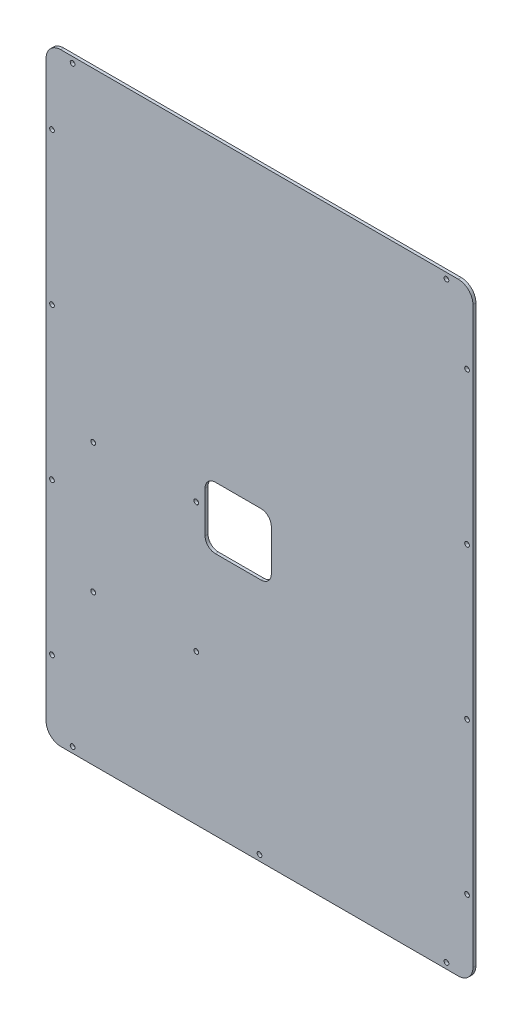
SolidWorks part; units mm, degrees
ref_plane "前视基准面" through (0, 0, 0) normal (0, 0, 1) x (1, 0, 0)
ref_plane "上视基准面" through (0, 0, 0) normal (0, 1, 0) x (1, 0, 0)
ref_plane "右视基准面" through (0, 0, 0) normal (1, 0, 0) x (0, 0, -1)
sketch "草图1" plane through (0, 0, 0) normal (0, 0, 1) x (1, 0, 0)
  line L1 (-58.971, 258.2107) -> (211.029, 258.2107)
  line L2 (-68.971, 248.2107) -> (-68.971, -141.7893)
  line L3 (-58.971, -151.7893) -> (211.029, -151.7893)
  line L4 (221.029, 248.2107) -> (221.029, -141.7893)
  arc A0 (-68.971, -141.7893) -> (-58.971, -151.7893) centre (-58.971, -141.7893) ccw
  arc A1 (211.029, -151.7893) -> (221.029, -141.7893) centre (211.029, -141.7893) ccw
  arc A2 (211.029, 258.2107) -> (221.029, 248.2107) centre (211.029, 248.2107) cw
  arc A3 (-58.971, 258.2107) -> (-68.971, 248.2107) centre (-58.971, 248.2107) ccw
  point P6 (-68.971, -151.7893)
  point P9 (221.029, -151.7893)
  point P14 (-68.971, 258.2107)
  dimension "D3" = 10
  dimension "D1" = 290
  dimension "D2" = 410
extrude "凸台-拉伸1" add sketch "草图1" along normal blind 2
sketch "草图2" plane through (0, 0, 2) normal (0, 0, 1) x (1, 0, 0)
  line L0 (-68.971, 248.2107) -> (-68.971, -141.7893) construction
  line L1 (211.029, 258.2107) -> (-58.971, 258.2107) construction
  line L2 (221.029, -141.7893) -> (221.029, 248.2107) construction
  line L3 (-58.971, -151.7893) -> (211.029, -151.7893) construction
  circle A0 centre (-64.971, 208.2107) radius 1.6
  circle A1 centre (-64.971, 105.2107) radius 1.6
  circle A2 centre (-64.971, 2.2107) radius 1.6
  circle A3 centre (-64.971, -100.7893) radius 1.6
  circle A4 centre (217.029, 208.2107) radius 1.6
  circle A5 centre (217.029, 105.2107) radius 1.6
  circle A6 centre (217.029, 2.2107) radius 1.6
  circle A7 centre (217.029, -100.7893) radius 1.6
  circle A8 centre (-50.971, 254.2107) radius 1.6
  circle A10 centre (203.029, 254.2107) radius 1.6
  circle A11 centre (-50.971, -147.7893) radius 1.6
  circle A12 centre (76.029, -147.7893) radius 1.6
  circle A13 centre (203.029, -147.7893) radius 1.6
  circle A14 centre (76.029, 254.2107) radius 1.6 [skipped]
  dimension "D1" = 3.2
  dimension "D5" = 4
  dimension "D11" = 3
  dimension "D2" = 4
  dimension "D3" = 50
  dimension "D6" = 4
  dimension "D7" = 4
  dimension "D8" = 18
  dimension "D10" = 4
  dimension "D4" = 4
  dimension "D9" = 3
extrude "切除-拉伸1" cut sketch "草图2" against normal through all
sketch "草图3" plane through (0, 0, 2) normal (0, 0, 1) x (1, 0, 0)
  line L0 (-68.971, 248.2107) -> (-68.971, -141.7893) construction
  line L1 (-58.971, -151.7893) -> (211.029, -151.7893) construction
  line L3 (46.029, 56.2107) -> (77.029, 56.2107)
  line L4 (39.029, 49.2107) -> (39.029, 21.2107)
  line L5 (46.029, 14.2107) -> (77.029, 14.2107)
  line L6 (84.029, 49.2107) -> (84.029, 21.2107)
  circle A0 centre (33.029, 38.2107) radius 1.6
  circle A1 centre (33.029, -49.7893) radius 1.6
  circle A2 centre (-36.971, -49.7893) radius 1.6
  circle A3 centre (-36.971, 38.2107) radius 1.6
  arc A4 (39.029, 21.2107) -> (46.029, 14.2107) centre (46.029, 21.2107) ccw
  arc A5 (77.029, 14.2107) -> (84.029, 21.2107) centre (77.029, 21.2107) ccw
  arc A6 (77.029, 56.2107) -> (84.029, 49.2107) centre (77.029, 49.2107) cw
  arc A7 (46.029, 56.2107) -> (39.029, 49.2107) centre (46.029, 49.2107) ccw
  point P8 (0, 0)
  point P19 (39.029, 14.2107)
  point P22 (84.029, 14.2107)
  point P25 (84.029, 56.2107)
  dimension "D2" = 3.2
  dimension "D11" = 7
  dimension "D1" = 70
  dimension "D3" = 88
  dimension "D4" = 88
  dimension "D5" = 32
  dimension "D6" = 190
  dimension "D7" = 42
  dimension "D8" = 45
  dimension "D9" = 6
  dimension "D10" = 18
extrude "切除-拉伸2" cut sketch "草图3" against normal through all
